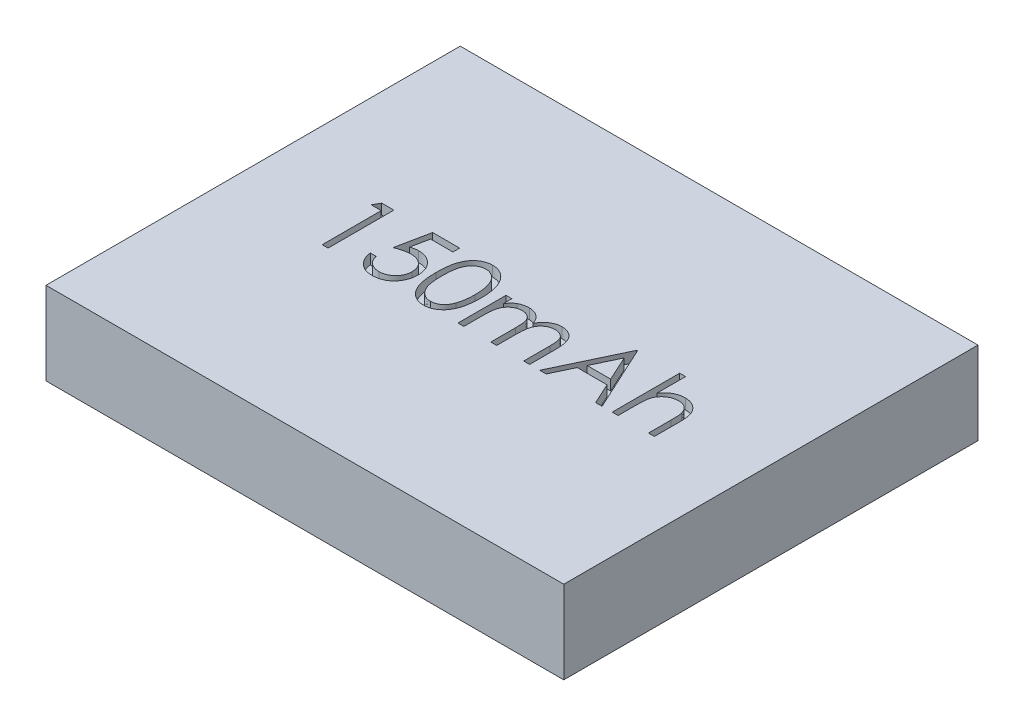
SolidWorks part; units mm, degrees
ref_plane "Front Plane" through (0, 0, 0) normal (0, 0, 1) x (1, 0, 0)
ref_plane "Top Plane" through (0, 0, 0) normal (0, 1, 0) x (1, 0, 0)
ref_plane "Right Plane" through (0, 0, 0) normal (1, 0, 0) x (0, 0, -1)
sketch "Sketch1" plane through (0, 0, 0) normal (0, 1, 0) x (1, 0, 0)
  line L1 (0, 0) -> (25, 0)
  line L2 (0, 0) -> (0, 20)
  line L3 (0, 20) -> (25, 20)
  line L4 (25, 0) -> (25, 20)
  dimension "D1" = 25
  dimension "D2" = 20
extrude "Boss-Extrude1" add sketch "Sketch1" along normal blind 4
sketch "Sketch2" plane through (0, 4, 0) normal (0, 1, 0) x (1, 0, 0)
  text T0 "150mAh"
extrude "Cut-Extrude1" cut sketch "Sketch2" against normal blind 0.5
